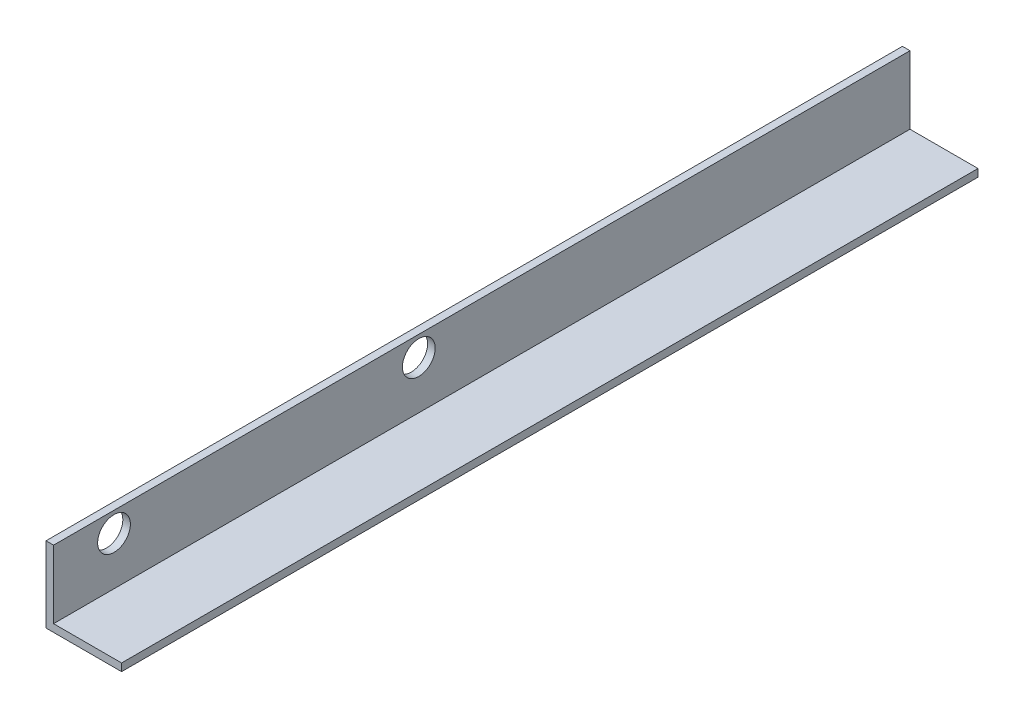
SolidWorks part; units mm, degrees
material "Ferro duttile"
ref_plane "Piano frontale" through (0, 0, 0) normal (0, 0, 1) x (1, 0, 0)
ref_plane "Piano superiore" through (0, 0, 0) normal (0, 1, 0) x (1, 0, 0)
ref_plane "Piano destro" through (0, 0, 0) normal (1, 0, 0) x (0, 0, -1)
sketch "Schizzo1" plane through (0, 0, 0) normal (0, 0, 1) x (1, 0, 0)
  line L0 (0, 30) -> (0, 0)
  line L1 (0, 0) -> (30, 0)
  line L2 (30, 0) -> (30, 3)
  line L3 (30, 3) -> (3, 3)
  line L4 (3, 3) -> (3, 30)
  line L5 (3, 30) -> (0, 30)
  dimension "D1" = 3
  dimension "D2" = 3
  dimension "D3" = 30
  dimension "D4" = 30
extrude "Estrusione-Estrusione1" add sketch "Schizzo1" along normal blind 340
sketch "Schizzo2" plane through (3, 0, 0) normal (1, 0, 0) x (0, 0, -1)
  circle A4 centre (-195, 22) radius 6.5
  circle A5 centre (-316, 22) radius 6.5
  dimension "D1" = 13
extrude "Taglio-Estrusione1" cut sketch "Schizzo2" against normal through all
